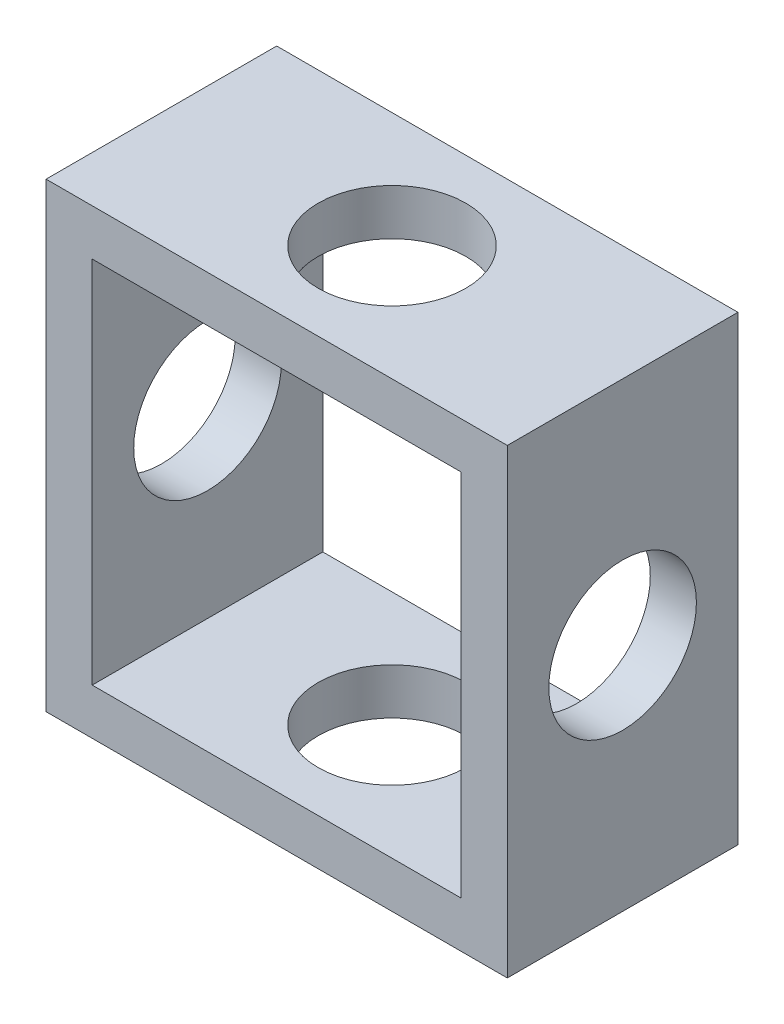
SolidWorks part; units mm, degrees
ref_plane "Alzado" through (0, 0, 0) normal (0, 0, 1) x (1, 0, 0)
ref_plane "Planta" through (0, 0, 0) normal (0, 1, 0) x (1, 0, 0)
ref_plane "Vista lateral" through (0, 0, 0) normal (1, 0, 0) x (0, 0, -1)
sketch "Croquis1" plane through (0, 0, 0) normal (0, 0, 1) x (1, 0, 0)
  line L1 (-20, 20) -> (20, 20)
  line L2 (-20, 20) -> (-20, -20)
  line L3 (-20, -20) -> (20, -20)
  line L4 (20, 20) -> (20, -20)
  line L5 (-20, 20) -> (20, -20) construction
  line L6 (-20, -20) -> (20, 20) construction
  line L7 (-25, 25) -> (25, 25)
  line L8 (-25, 25) -> (-25, -25)
  line L9 (-25, -25) -> (25, -25)
  line L10 (25, 25) -> (25, -25)
  line L11 (-25, 25) -> (25, -25) construction
  line L12 (-25, -25) -> (25, 25) construction
  point P0 (0, 0)
  point P6 (0, 0)
  dimension "D1" = 50
  dimension "D2" = 50
  dimension "D3" = 40
  dimension "D4" = 40
extrude "Saliente-Extruir1" add sketch "Croquis1" along normal blind 25
sketch "Croquis2" plane through (0, 25, 0) normal (0, 1, 0) x (1, 0, 0)
  circle A0 centre (0, -12.5) radius 8
  dimension "D1" = 16
extrude "Cortar-Extruir1" cut sketch "Croquis2" against normal blind 60
sketch "Croquis3" plane through (25, 0, 0) normal (1, 0, 0) x (0, 0, -1)
  circle A0 centre (-12.5, 0) radius 8
  dimension "D1" = 16
extrude "Cortar-Extruir2" cut sketch "Croquis3" against normal blind 60
